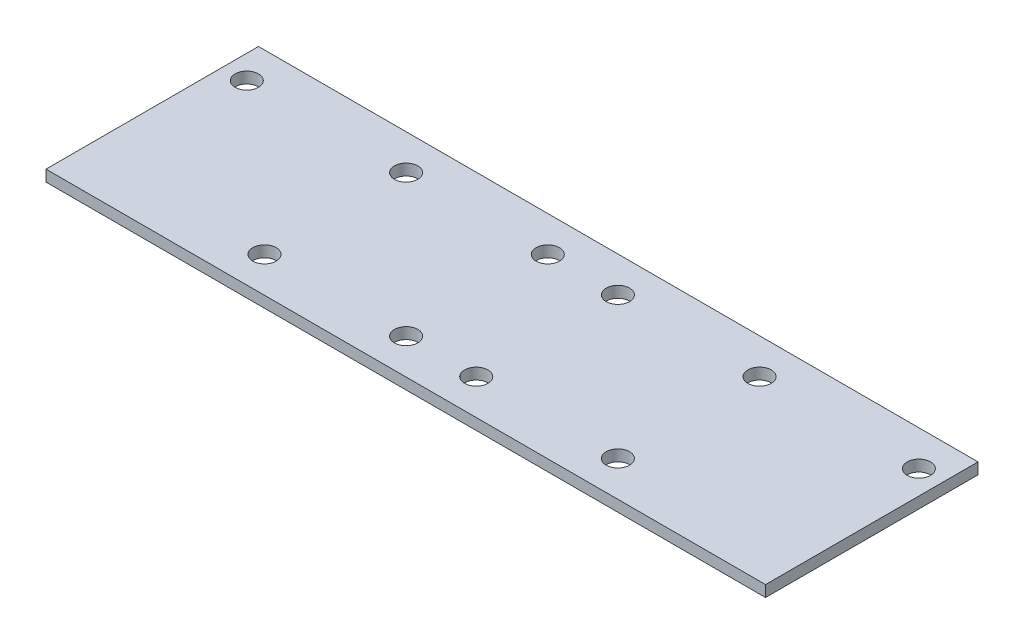
SolidWorks part; units mm, degrees
ref_plane "Front Plane" through (0, 0, 0) normal (0, 0, 1) x (1, 0, 0)
ref_plane "Top Plane" through (0, 0, 0) normal (0, 1, 0) x (1, 0, 0)
ref_plane "Right Plane" through (0, 0, 0) normal (1, 0, 0) x (0, 0, -1)
sketch "Sketch1" plane through (0, 0, 0) normal (0, 1, 0) x (1, 0, 0)
  line L1 (-101.6, 30) -> (101.6, 30)
  line L2 (-101.6, 30) -> (-101.6, -30)
  line L3 (-101.6, -30) -> (101.6, -30)
  line L4 (101.6, 30) -> (101.6, -30)
  line L5 (-101.6, 30) -> (101.6, -30) construction
  line L6 (-101.6, -30) -> (101.6, 30) construction
  line L7 (0, 0) -> (0, 23.5578) construction
  circle A0 centre (-49.9, 20) radius 3.3
  circle A1 centre (-9.9, 20) radius 3.3
  circle A2 centre (-9.9, -20) radius 3.3
  circle A3 centre (-49.9, -20) radius 3.3
  circle A4 centre (-94.9, 20) radius 3.3
  circle A5 centre (94.9, 20) radius 3.3
  circle A6 centre (49.9, -20) radius 3.3
  circle A7 centre (9.9, -20) radius 3.3
  circle A8 centre (9.9, 20) radius 3.3
  circle A9 centre (49.9, 20) radius 3.3
  point P0 (0, 0)
  dimension "D1" = 6.6
  dimension "D2" = 40
  dimension "D3" = 40
  dimension "D5" = 45
  dimension "D6" = 60
  dimension "D7" = 6.7
  dimension "D8" = 203.2
  dimension "D9" = 10
extrude "Boss-Extrude1" add sketch "Sketch1" along normal blind 3.175
